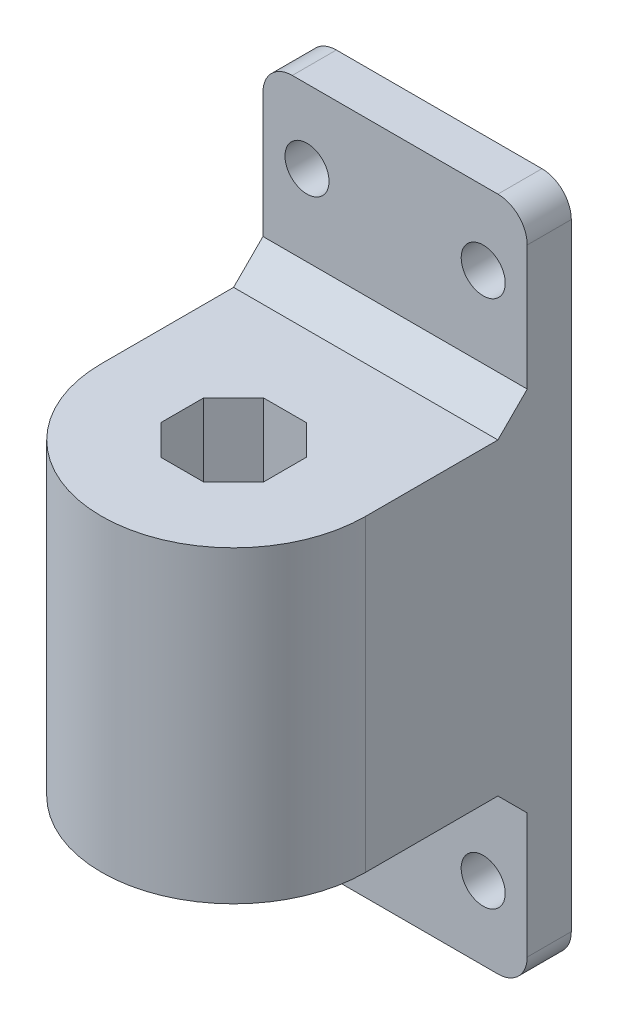
SolidWorks part; units mm, degrees
ref_plane "Front Plane" through (0, 0, 0) normal (0, 0, 1) x (1, 0, 0)
ref_plane "Top Plane" through (0, 0, 0) normal (0, 1, 0) x (1, 0, 0)
ref_plane "Right Plane" through (0, 0, 0) normal (1, 0, 0) x (0, 0, -1)
sketch "Sketch1" plane through (0, 0, 0) normal (0, 1, 0) x (1, 0, 0)
  line L0 (-9, 0) -> (9, 0)
  line L1 (0, -14) -> (0, 0) construction
  line L2 (-2.7424, -9.25) -> (-5.4848, -14)
  line L3 (-5.4848, -14) -> (-2.7424, -18.75)
  line L4 (-2.7424, -18.75) -> (2.7424, -18.75)
  line L5 (2.7424, -18.75) -> (5.4848, -14)
  line L6 (5.4848, -14) -> (2.7424, -9.25)
  line L7 (2.7424, -9.25) -> (-2.7424, -9.25)
  line L8 (-9, 0) -> (-9, -14)
  line L9 (9, -14) -> (9, 0)
  circle A0 centre (0, -14) radius 4.75 construction
  arc A1 (-9, -14) -> (9, -14) centre (0, -14) ccw
  point P14 (9, -7)
  dimension "D1" = 9.5
  dimension "D2" = 14
  dimension "D3" = 18
extrude "Boss-Extrude1" add sketch "Sketch1" along normal blind 21
sketch "Sketch2" plane through (0, 21, 0) normal (0, 1, 0) x (1, 0, 0)
  line L0 (3.5, -12.5503) -> (1.4497, -10.5)
  line L1 (-1.4497, -10.5) -> (-3.5, -12.5503)
  line L2 (-3.5, -12.5503) -> (-3.5, -15.4497)
  line L3 (-3.5, -15.4497) -> (-1.4497, -17.5)
  line L4 (-1.4497, -17.5) -> (1.4497, -17.5)
  line L5 (1.4497, -17.5) -> (3.5, -15.4497)
  line L6 (3.5, -15.4497) -> (3.5, -12.5503)
  line L7 (1.4497, -10.5) -> (-1.4497, -10.5)
  circle A0 centre (0, -14) radius 9
  arc A2 (-9, -14) -> (9, -14) centre (0, -14) ccw construction
  circle A3 centre (0, -14) radius 3.5 construction
  dimension "D1" = 7
extrude "Boss-Extrude2" add sketch "Sketch2" against normal offset from surface (17 mm away) 4 up to face at (0, 0, 9.25)
sketch "Sketch4" plane through (0, 0, 0) normal (0, 0, -1) x (-1, 0, 0)
  line L0 (-9, 10.5) -> (9, 10.5) construction
  line L1 (-9, 21) -> (9, 21)
  line L2 (-9, 21) -> (-9, 33.5)
  line L3 (-9, 33.5) -> (9, 33.5)
  line L4 (-6, 28.5) -> (6, 28.5) construction
  line L5 (9, 21) -> (9, 33.5)
  line L6 (-9, 21) -> (-9, 0) construction
  line L7 (9, 21) -> (9, 0) construction
  line L8 (0, 28.5) -> (0, 21) construction
  line L9 (0, -7.5) -> (0, 0) construction
  line L10 (-6, -7.5) -> (6, -7.5) construction
  line L11 (9, 0) -> (9, -12.5)
  line L12 (-9, -12.5) -> (9, -12.5)
  line L13 (-9, 0) -> (-9, -12.5)
  line L14 (-9, 0) -> (9, 0)
  circle A0 centre (-6, 28.5) radius 1.5
  circle A1 centre (6, 28.5) radius 1.5
  circle A2 centre (6, -7.5) radius 1.5
  circle A3 centre (-6, -7.5) radius 1.5
  dimension "D1" = 18
  dimension "D3" = 3
  dimension "D2" = 12
  dimension "D4" = 5
extrude "Boss-Extrude3" add sketch "Sketch4" against normal blind 3
fillet "Fillet1" radius 2 4 edges at (9, -12.5, 1.5) (-9, -12.5, 1.5) (9, 33.5, 1.5) (-9, 33.5, 1.5)
chamfer "Chamfer1" distance 2 angle 45 2 edges at (0, 21, 3) (0, 0, 3)
